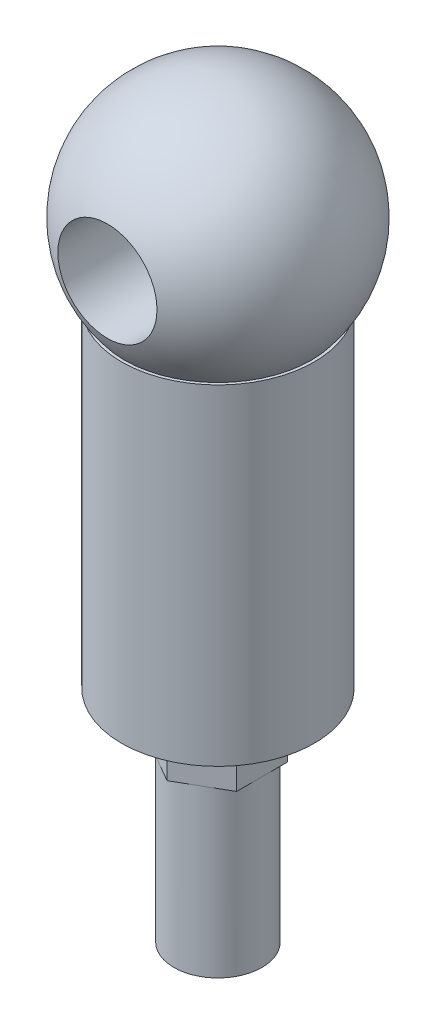
SolidWorks part; units mm, degrees
ref_plane "前视基准面" through (0, 0, 0) normal (0, 0, 1) x (1, 0, 0)
ref_plane "上视基准面" through (0, 0, 0) normal (0, 1, 0) x (1, 0, 0)
ref_plane "右视基准面" through (0, 0, 0) normal (1, 0, 0) x (0, 0, -1)
sketch "草图1" plane through (0, 0, 0) normal (0, 1, 0) x (1, 0, 0)
  line L1 (0, 4.6188) -> (-4, 2.3094)
  line L2 (-4, 2.3094) -> (-4, -2.3094)
  line L3 (-4, -2.3094) -> (0, -4.6188)
  line L4 (0, -4.6188) -> (4, -2.3094)
  line L5 (4, -2.3094) -> (4, 2.3094)
  line L6 (4, 2.3094) -> (0, 4.6188)
  circle A0 centre (0, 0) radius 4 construction
  dimension "D1" = 8
extrude "凸台-拉伸1" add sketch "草图1" along normal blind 5
sketch "草图2" plane through (0, 5, 0) normal (0, 1, 0) x (1, 0, 0)
  circle A0 centre (0, 0) radius 8.75
  dimension "D1" = 17.5
extrude "凸台-拉伸2" add sketch "草图2" along normal blind 30
sketch "草图3" plane through (0, 0, 0) normal (0, 0, 1) x (1, 0, 0)
  line L0 (0, 53) -> (0, 0)
  arc A0 (0, 31) -> (0, 53) centre (0, 42) ccw
  dimension "D2" = 22
  dimension "D1" = 42
revolve "旋转1" add sketch "草图3" angle 360 about L0
sketch "草图4" plane through (0, 0, 0) normal (0, 0, 1) x (1, 0, 0)
  circle A0 centre (0, 42) radius 4.5
  circle A1 centre (0, 42) radius 11 construction
  dimension "D1" = 9
extrude "切除-拉伸1" cut sketch "草图4" against normal mid plane 50
sketch "草图5" plane through (0, 0, 0) normal (0, -1, 0) x (1, 0, 0)
  circle A0 centre (0, 0) radius 4
  dimension "D1" = 8
extrude "凸台-拉伸3" add sketch "草图5" along normal blind 15
